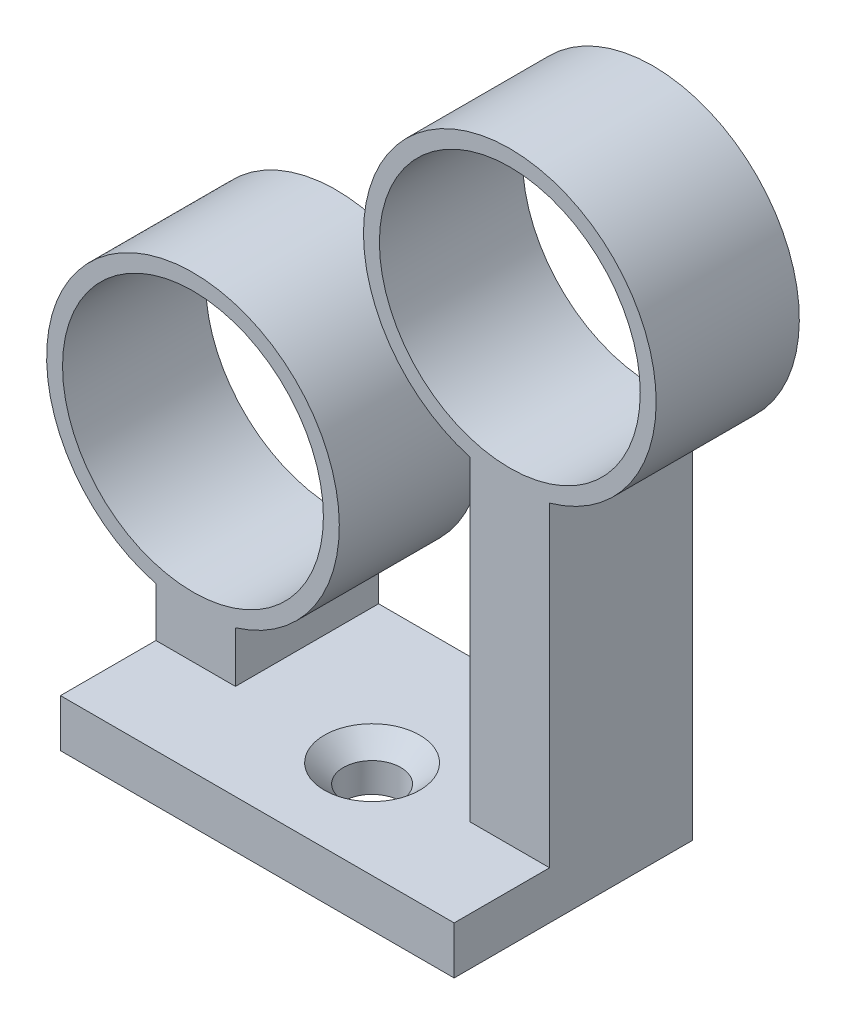
SolidWorks part; units mm, degrees
ref_plane "Alzado" through (0, 0, 0) normal (0, 0, 1) x (1, 0, 0)
ref_plane "Planta" through (0, 0, 0) normal (0, 1, 0) x (1, 0, 0)
ref_plane "Vista lateral" through (0, 0, 0) normal (1, 0, 0) x (0, 0, -1)
sketch "Sketch1" plane through (0, 0, 0) normal (0, 0, 1) x (1, 0, 0)
  line L0 (0.295, 24.8228) -> (61.4006, 24.8228) construction
  circle A0 centre (2.6252, 39.8228) radius 8.2
  circle A1 centre (22.5445, 56.5328) radius 8.2
  circle A3 centre (22.5445, 56.5328) radius 9.2
  circle A7 centre (2.6252, 39.8228) radius 9.2
  dimension "D3" = 16.4
  dimension "D5" = 16.4
  dimension "D4" = 18.4
  dimension "D1" = 18.4
  dimension "D6" = 26
  dimension "D7" = 31.71
extrude "Boss-Extrude1" add sketch "Sketch1" along normal blind 9
sketch "Sketch2" plane through (0, 0, 0) normal (0, 0, 1) x (1, 0, 0)
  line L1 (0.295, 24.8228) -> (5.295, 24.8228)
  line L2 (0.295, 24.8228) -> (0.295, 30.9228)
  line L4 (5.295, 24.8228) -> (5.295, 31.0187)
  line L7 (20.0445, 47.7228) -> (20.0445, 24.8228)
  line L8 (20.0445, 24.8228) -> (25.0445, 24.8228)
  line L9 (25.0445, 47.7228) -> (25.0445, 24.8228)
  arc A6 (20.0445, 47.7228) -> (25.0445, 47.7228) centre (22.5445, 55.5406) ccw
  arc A7 (0.295, 30.9228) -> (5.295, 31.0187) centre (2.6252, 39.8228) ccw
  dimension "D1" = 5
  dimension "D2" = 6.1
  dimension "D8" = 5
  dimension "D9" = 22.9
  dimension "D10" = 22.9
extrude "Boss-Extrude2" add sketch "Sketch2" along normal blind 9
sketch "Sketch3" plane through (0, 24.8228, 0) normal (0, -1, 0) x (1, 0, 0)
  line L1 (0.295, 15) -> (25.0445, 15)
  line L2 (0.295, 15) -> (0.295, 0)
  line L3 (0.295, 0) -> (25.0445, 0)
  line L4 (25.0445, 15) -> (25.0445, 0)
  dimension "D1" = 24.7495
  dimension "D2" = 15
extrude "Boss-Extrude3" add sketch "Sketch3" against normal blind 3
hole_wizard "Avellanado para tornillo con cabeza avellanada en cruz de M31" positions "3DSketch1" profile "Sketch4" countersink size "M3" standard "AS"
sketch3d "3DSketch1"
  point P0 (13.742, 27.8228, 8.8563)
sketch "Sketch4" plane through (13.742, 27.8228, 8.8563) normal (1, 0, 0) x (0, 0, 1)
  line L0 (0, 0) -> (0, 11.0815)
  line L1 (0, 11.0815) -> (1.8, 10)
  line L2 (1.8, 10) -> (1.8, 1.1588)
  line L3 (1.8, 1.1588) -> (3, 0)
  line L5 (3, 0) -> (0, 0)
  line L6 (-1.8, 1.1588) -> (-3, 0) construction
  line L10 (0, 11.0815) -> (-1.8, 10) construction
  line L11 (0, -6.35) -> (0, 107.95) construction
  dimension "Diámetro de taladro" = 3.6
  dimension "Profundidad de taladro" = 10
  dimension "Ángulo de avellanado cercano" = 6
  dimension "Ángulo de avellanado lejano" = 92
  dimension "Ángulo de perforador" = 118
